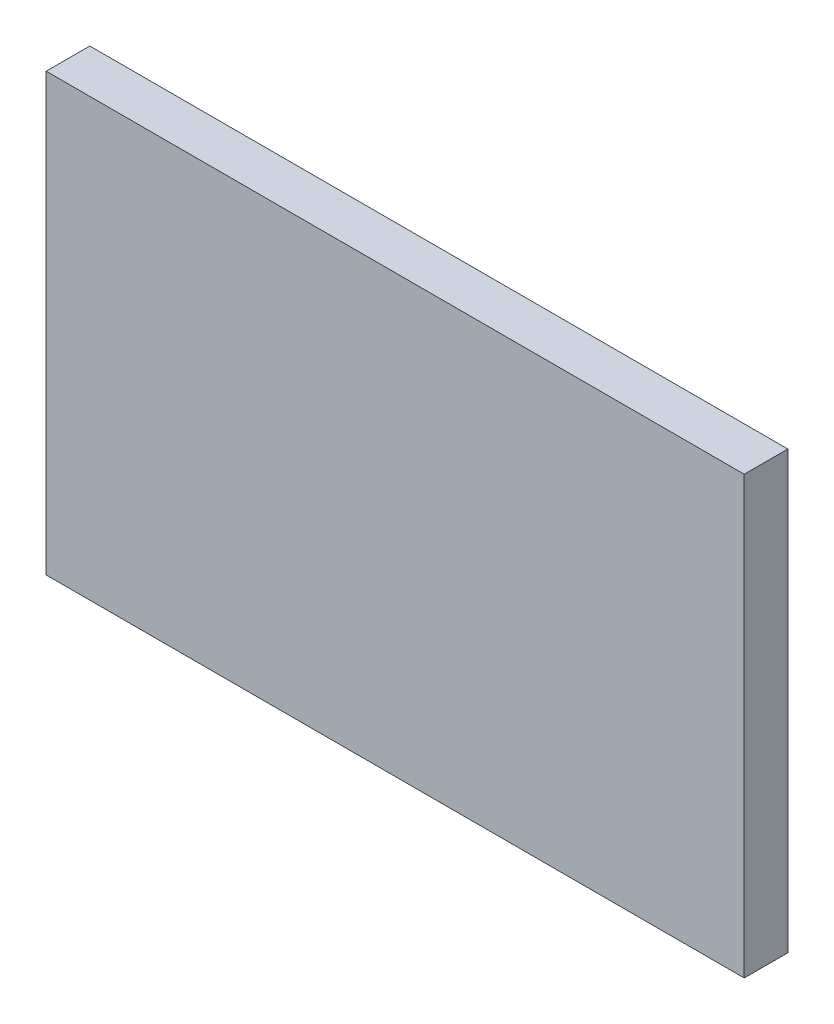
SolidWorks part; units mm, degrees
ref_plane "Front Plane" through (0, 0, 0) normal (0, 0, 1) x (1, 0, 0)
ref_plane "Top Plane" through (0, 0, 0) normal (0, 1, 0) x (1, 0, 0)
ref_plane "Right Plane" through (0, 0, 0) normal (1, 0, 0) x (0, 0, -1)
sketch "Sketch1" plane through (0, 0, 0) normal (0, 0, 1) x (1, 0, 0)
  line L1 (0, 0) -> (101.6, 0)
  line L2 (0, 0) -> (0, 63.5)
  line L3 (0, 63.5) -> (101.6, 63.5)
  line L4 (101.6, 0) -> (101.6, 63.5)
  dimension "D1" = 101.6
  dimension "D2" = 63.5
extrude "Boss-Extrude1" add sketch "Sketch1" along normal blind 6.35
